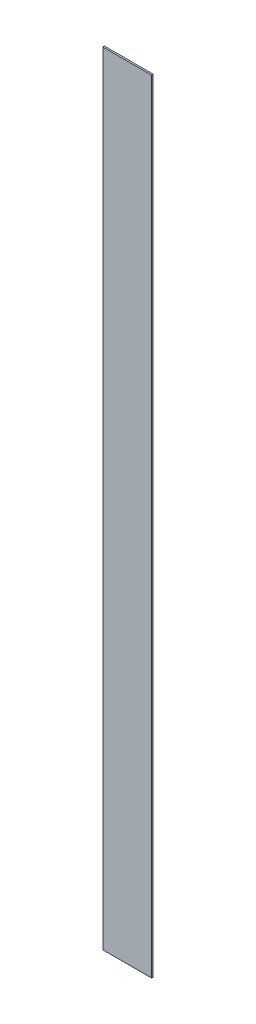
SolidWorks part; units mm, degrees
ref_plane "Front Plane" through (0, 0, 0) normal (0, 0, 1) x (1, 0, 0)
ref_plane "Top Plane" through (0, 0, 0) normal (0, 1, 0) x (1, 0, 0)
ref_plane "Right Plane" through (0, 0, 0) normal (1, 0, 0) x (0, 0, -1)
sketch "Sketch1" plane through (0, 0, 0) normal (0, 0, 1) x (1, 0, 0)
  line L1 (-37.5, 600) -> (37.5, 600)
  line L2 (-37.5, 600) -> (-37.5, -600)
  line L3 (-37.5, -600) -> (37.5, -600)
  line L4 (37.5, 600) -> (37.5, -600)
  line L5 (-37.5, 600) -> (37.5, -600) construction
  line L6 (-37.5, -600) -> (37.5, 600) construction
  point P0 (0, 0)
  dimension "D1" = 1200
  dimension "D2" = 75
extrude "Boss-Extrude1" add sketch "Sketch1" along normal blind 2.5
